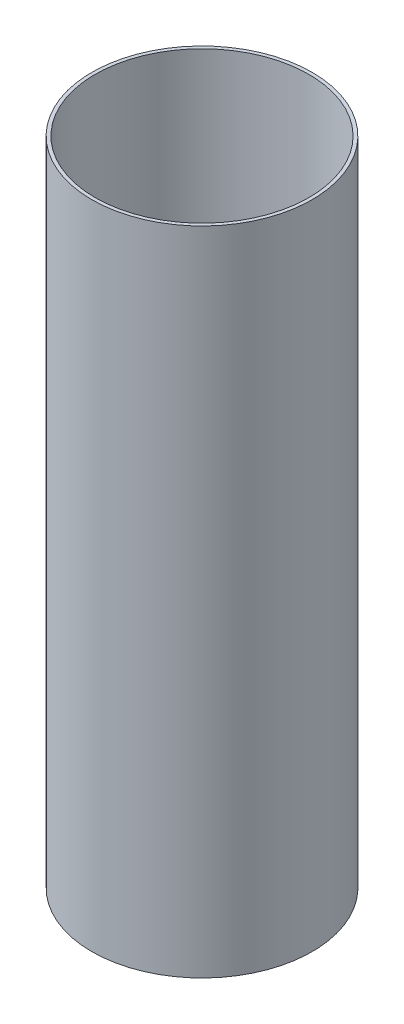
SolidWorks part; units mm, degrees
material "HYPALON"
ref_plane "Płaszczyzna przednia" through (0, 0, 0) normal (0, 0, 1) x (1, 0, 0)
ref_plane "Płaszczyzna górna" through (0, 0, 0) normal (0, 1, 0) x (1, 0, 0)
ref_plane "Płaszczyzna prawa" through (0, 0, 0) normal (1, 0, 0) x (0, 0, -1)
sketch "Szkic1" plane through (0, 0, 0) normal (0, 0, 1) x (1, 0, 0)
  line L16 (0, 150) -> (0, -150) construction
  line L17 (0, 0) -> (63, 0) construction
  line L18 (63, 192) -> (65, 192)
  line L19 (63, 192) -> (63, -192)
  line L20 (63, -192) -> (65, -192)
  line L21 (65, 192) -> (65, -192)
  point P8 (0, 0)
  dimension "D1" = 65
  dimension "D2" = 2
  dimension "D3" = 384
revolve "Obrót1" add sketch "Szkic1" angle 360 about L16
